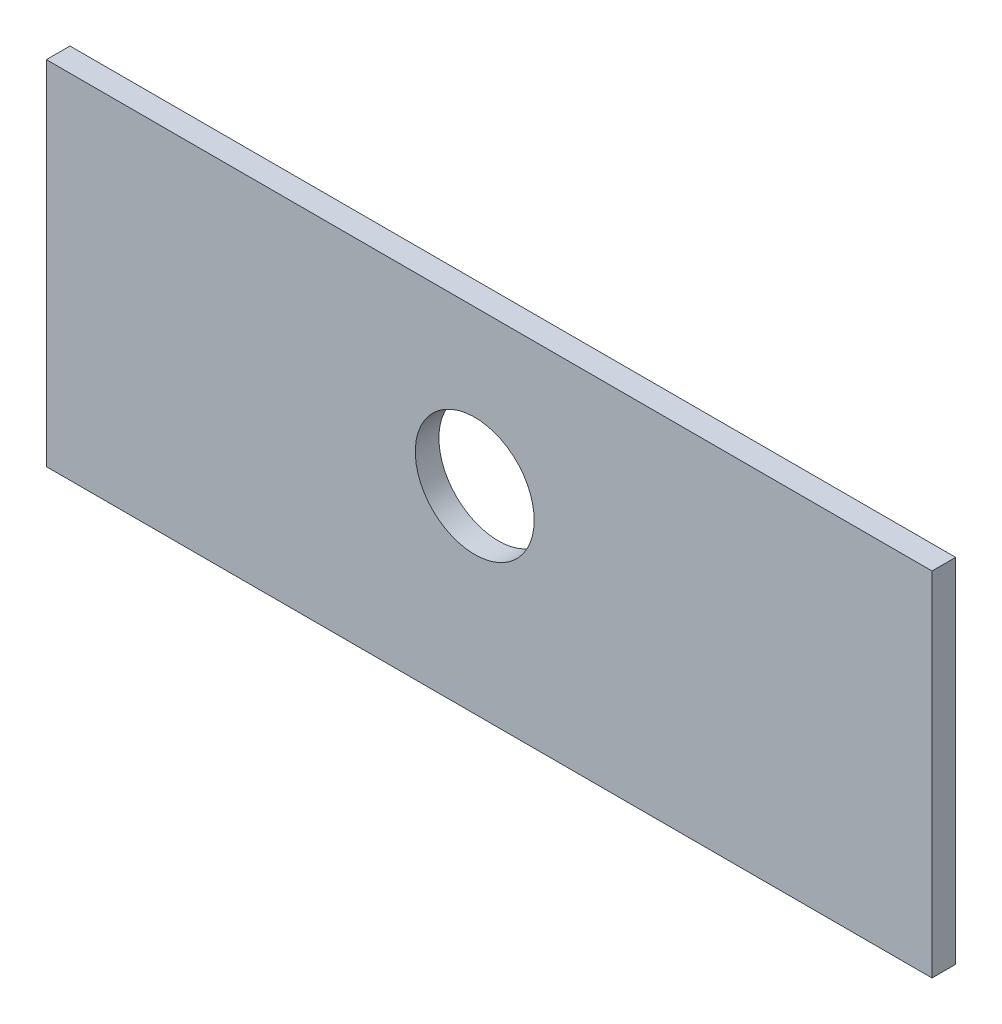
SolidWorks part; units mm, degrees
ref_plane "Front Plane" through (0, 0, 0) normal (0, 0, 1) x (1, 0, 0)
ref_plane "Top Plane" through (0, 0, 0) normal (0, 1, 0) x (1, 0, 0)
ref_plane "Right Plane" through (0, 0, 0) normal (1, 0, 0) x (0, 0, -1)
sketch "Sketch1" plane through (0, 0, 0) normal (0, 0, 1) x (1, 0, 0)
  line L0 (29.7413, 7.5406) -> (-45.2587, 7.5406)
  line L1 (-45.2587, 7.5406) -> (-45.2587, 37.391)
  line L2 (-45.2587, 37.391) -> (29.7413, 37.391)
  line L3 (29.7413, 37.391) -> (29.7413, 7.5406)
  circle A0 centre (-8.9833, 24.2669) radius 5.0347
  dimension "D1" = 75
extrude "Boss-Extrude1" add sketch "Sketch1" along normal blind 2
